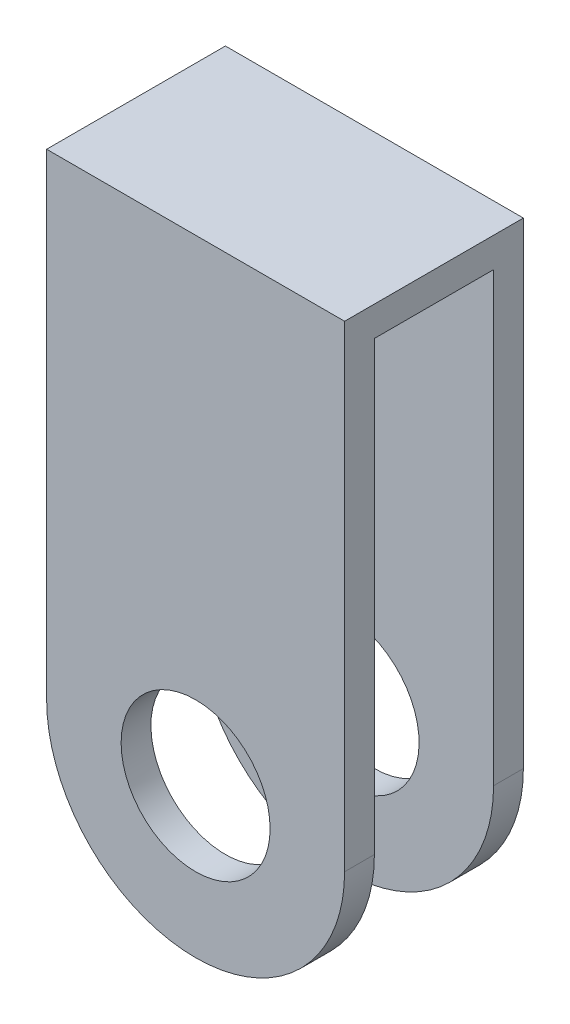
SolidWorks part; units mm, degrees
material "1060 Alloy"
ref_plane "Front" through (0, 0, 0) normal (0, 0, 1) x (1, 0, 0)
ref_plane "Top" through (0, 0, 0) normal (0, 1, 0) x (1, 0, 0)
ref_plane "Right" through (0, 0, 0) normal (1, 0, 0) x (0, 0, -1)
sketch "Sketch1" plane through (0, 0, 0) normal (0, 0, 1) x (1, 0, 0)
  line L4 (0, 12.2335) -> (15.8227, 12.2335) construction
  line L5 (-2.0886, 12.2335) -> (-2.0886, 44.2335)
  line L6 (-2.0886, 44.2335) -> (17.9114, 44.2335)
  line L7 (17.9114, 44.2335) -> (17.9114, 12.2335)
  circle A0 centre (7.9114, 12.2335) radius 5
  arc A1 (-2.0886, 12.2335) -> (17.9114, 12.2335) centre (7.9114, 12.2335) ccw
  circle A2 centre (7.9114, 12.2335) radius 10 construction
  dimension "D1" = 5
  dimension "D2" = 32
extrude "Boss-Extrude1" add sketch "Sketch1" along normal blind 12
sketch "Sketch2" plane through (-2.0886, 0, 0) normal (-1, 0, 0) x (0, 0, 1)
  line L3 (0, 44.2335) -> (0, 12.2335) construction
  line L4 (12, 44.2335) -> (0, 44.2335) construction
  line L7 (2, 42.2335) -> (10, 42.2335)
  line L8 (2, 42.2335) -> (2, 0)
  line L9 (2, 0) -> (10, 0)
  line L10 (10, 42.2335) -> (10, 0)
  dimension "D1" = 2
  dimension "D2" = 8
  dimension "D3" = 2
extrude "Cut-Extrude1" cut sketch "Sketch2" against normal up to surface (20 mm away) contours L8 L9 L10 L7 up to face at (17.9114, 28.2335, 6)
